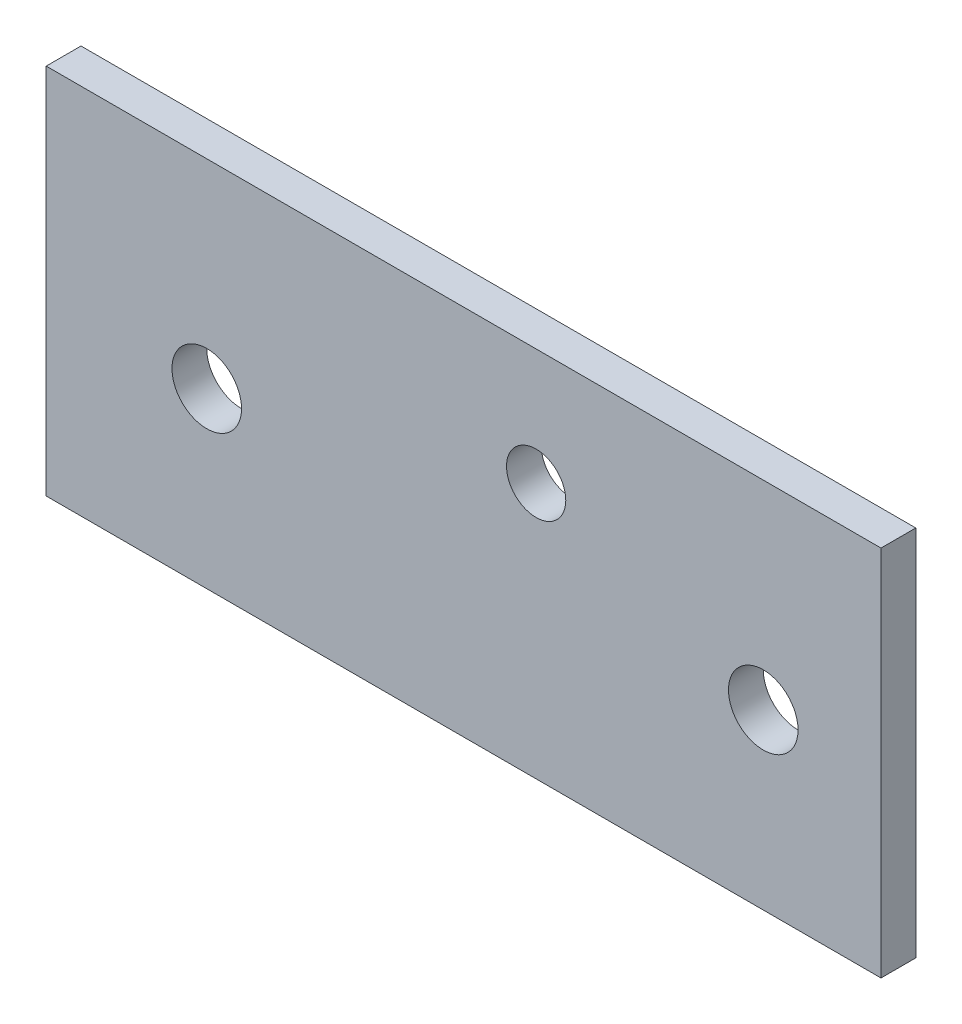
SolidWorks part; units mm, degrees
ref_plane "Front Plane" through (0, 0, 0) normal (0, 0, 1) x (1, 0, 0)
ref_plane "Top Plane" through (0, 0, 0) normal (0, 1, 0) x (1, 0, 0)
ref_plane "Right Plane" through (0, 0, 0) normal (1, 0, 0) x (0, 0, -1)
sketch "Sketch1" plane through (0, 0, 0) normal (0, 0, 1) x (1, 0, 0)
  line L1 (10.747, -276.6534) -> (86.947, -276.6534)
  line L2 (10.747, -276.6534) -> (10.747, -310.6424)
  line L3 (10.747, -310.6424) -> (86.947, -310.6424)
  line L4 (86.947, -276.6534) -> (86.947, -310.6424)
  circle A0 centre (25.4, -294.8214) radius 3.175
  circle A1 centre (76.2, -294.8214) radius 3.175
  dimension "D1" = 6.35
  dimension "D2" = 6.35
  dimension "D3" = 76.2
  dimension "D4" = 33.989
  dimension "D5" = 15.821
  dimension "D6" = 10.747
extrude "Boss-Extrude1" add sketch "Sketch1" along normal blind 3.175
hole_wizard "1/4-28 Tapped Hole1" positions "Sketch4" profile "Sketch3" tap size "1/4-28" standard "ANSI Inch" end condition through all
sketch "Sketch4" plane through (0, 0, 3.175) normal (0, 0, 1) x (1, 0, 0)
  point P0 (55.4677, -287.2734)
sketch "Sketch3" plane through (55.4677, -287.2734, 3.175) normal (1, 0, 0) x (0, -1, 0)
  line L0 (0, 0) -> (0, 3.175)
  line L1 (0, 3.175) -> (2.7051, 3.175)
  line L2 (2.7051, 3.175) -> (2.7051, 0)
  line L5 (2.7051, 0) -> (0, 0)
  line L11 (0, -6.35) -> (0, 107.95) construction
  dimension "Thru Tap Drill Dia." = 5.4102
  dimension "Thru Tap Drill Depth" = 3.175
